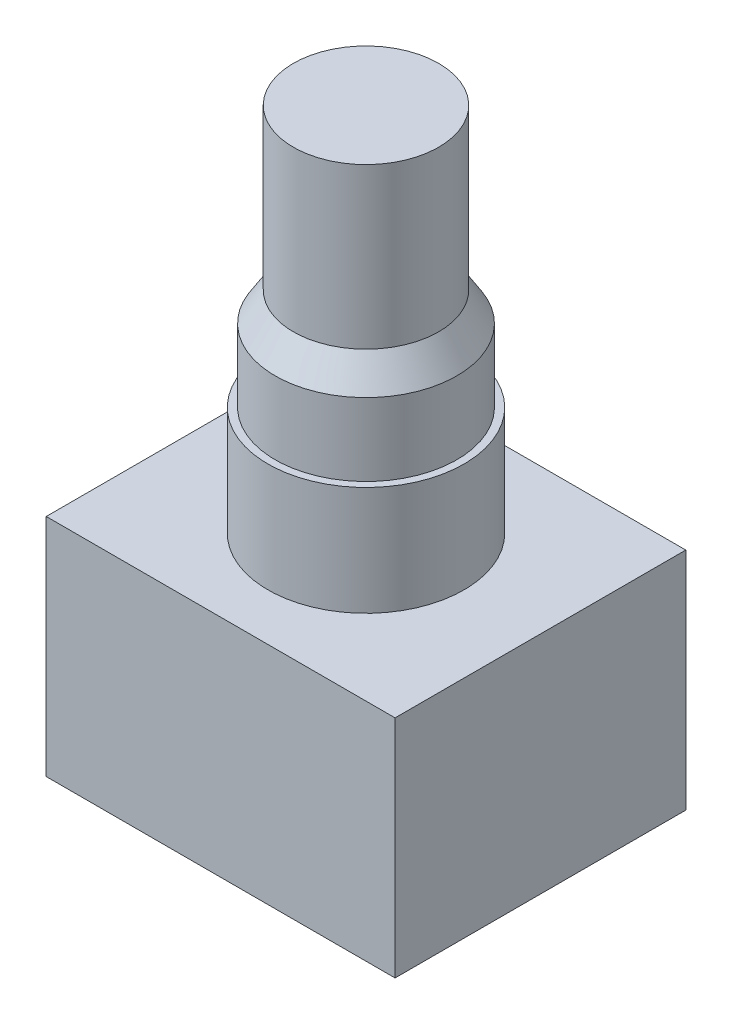
SolidWorks part; units mm, degrees
ref_plane "Front Plane" through (0, 0, 0) normal (0, 0, 1) x (1, 0, 0)
ref_plane "Top Plane" through (0, 0, 0) normal (0, 1, 0) x (1, 0, 0)
ref_plane "Right Plane" through (0, 0, 0) normal (1, 0, 0) x (0, 0, -1)
sketch "Sketch1" plane through (0, 0, 0) normal (0, 1, 0) x (1, 0, 0)
  line L1 (6.096, -5.08) -> (-6.096, -5.08)
  line L2 (6.096, -5.08) -> (6.096, 5.08)
  line L3 (6.096, 5.08) -> (-6.096, 5.08)
  line L4 (-6.096, -5.08) -> (-6.096, 5.08)
  line L5 (6.096, -5.08) -> (-6.096, 5.08) construction
  line L6 (6.096, 5.08) -> (-6.096, -5.08) construction
  point P0 (0, 0)
  dimension "D1" = 10.16
  dimension "D2" = 12.192
extrude "Boss-Extrude1" add sketch "Sketch1" against normal blind 7.874
sketch "Sketch2" plane through (0, 0, 0) normal (1, 0, 0) x (0, 0, -1)
  line L0 (0, 0) -> (0, 12.954) construction
  line L1 (-5.08, 0) -> (5.08, 0) construction
  line L2 (0, 0) -> (3.429, 0)
  line L3 (3.429, 0) -> (3.429, 3.81)
  line L4 (3.429, 3.81) -> (3.175, 3.81)
  line L5 (3.175, 3.81) -> (3.175, 6.35)
  line L6 (3.175, 6.35) -> (2.54, 7.366)
  line L7 (2.54, 7.366) -> (2.54, 12.954)
  line L8 (2.54, 12.954) -> (0, 12.954)
  line L9 (0, 0) -> (0, 12.954)
  point P4 (0, 11.3773)
  point P11 (0, 0)
  point P12 (3.556, 3.9226)
  point P13 (3.556, 2.1447)
  point P14 (3.556, 3.6419)
  point P15 (2.54, 4.3156)
  point P16 (3.175, 4.6151)
  point P17 (3.175, 4.4654)
  dimension "D1" = 3.429
  dimension "D2" = 0.254
  dimension "D3" = 2.54
  dimension "D4" = 12.954
  dimension "D5" = 5.588
  dimension "D6" = 2.54
  dimension "D7" = 3.81
revolve "Revolve1" add sketch "Sketch2" angle 360 about L0
